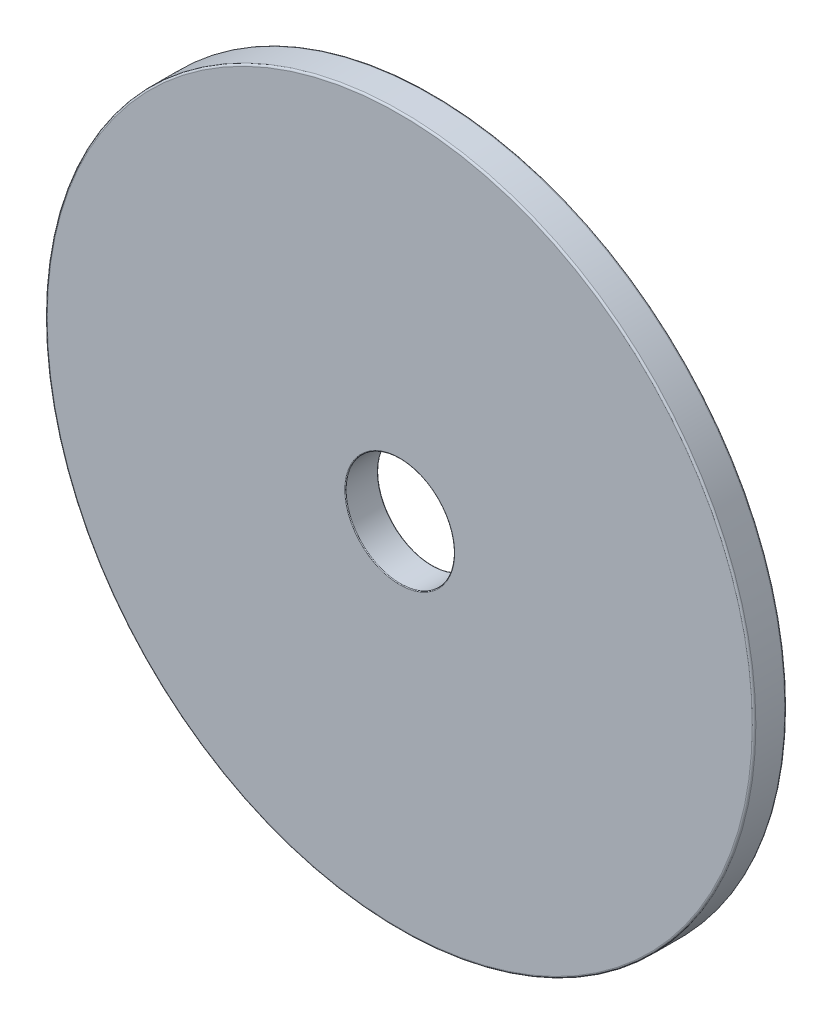
SolidWorks part; units mm, degrees
other "Markup1"
sketch "Sketch7" plane through (500, -500, -17.5) normal (0.1872, -0.6574, -0.7299) x (-0.982, -0.143, -0.123)
material "Portland Moderate Strength Concrete"
ref_plane "Front Plane" through (0, 0, 0) normal (0, 0, 1) x (1, 0, 0)
ref_plane "Top Plane" through (0, 0, 0) normal (0, 1, 0) x (1, 0, 0)
ref_plane "Right Plane" through (0, 0, 0) normal (1, 0, 0) x (0, 0, -1)
sketch "Sketch1" plane through (0, 0, 0) normal (0, 1, 0) x (1, 0, 0)
  line L0 (0, 58.8545) -> (0, -44.381) construction
  line L1 (-490, 20) -> (-490, -20)
  line L2 (-487.5, -22.5) -> (-150, -22.5)
  line L4 (47.8242, 0) -> (-116.8517, 0) construction
  line L5 (-487.5, 22.5) -> (-261, 22.5)
  line L8 (-76, 22.5) -> (-150, 22.5)
  line L15 (-76, -22.5) -> (-150, -22.5)
  line L16 (-75, 21.5) -> (-75, -21.5)
  line L17 (-260, 21.5) -> (-260, 13.5)
  line L18 (-259, 12.5) -> (-231, 12.5)
  line L19 (-230, 13.5) -> (-230, 21.5)
  line L20 (-229, 22.5) -> (-150, 22.5)
  arc A2 (-490, -20) -> (-487.5, -22.5) centre (-487.5, -20) ccw
  arc A3 (-490, 20) -> (-487.5, 22.5) centre (-487.5, 20) cw
  arc A4 (-76, -22.5) -> (-75, -21.5) centre (-76, -21.5) ccw
  arc A5 (-75, 21.5) -> (-76, 22.5) centre (-76, 21.5) ccw
  arc A6 (-229, 22.5) -> (-230, 21.5) centre (-229, 21.5) ccw
  arc A7 (-230, 13.5) -> (-231, 12.5) centre (-231, 13.5) cw
  arc A8 (-260, 13.5) -> (-259, 12.5) centre (-259, 13.5) ccw
  arc A9 (-261, 22.5) -> (-260, 21.5) centre (-261, 21.5) cw
  point P9 (-490, 0)
  point P29 (-230, 22.5)
  point P32 (-230, 12.5)
  point P35 (-260, 12.5)
  point P38 (-260, 22.5)
  dimension "D1" = 40
  dimension "D2" = 1
  dimension "D5" = 2.5
  dimension "D3" = 490
  dimension "D7" = 150
  dimension "D8" = 30
  dimension "D9" = 10
  dimension "D10" = 230
revolve "Revolve1" add sketch "Sketch1" angle 360 about L0
sketch "Sketch6" plane through (0, 0, -22.5) normal (0, 0, -1) x (-1, 0, 0)
  line L0 (0, 0) -> (-674.8433, 0) construction
  line L1 (-456.4497, 57.0406) -> (-357.3025, 43.9876)
  line L2 (-456.4497, -57.0406) -> (-357.3025, -43.9876)
  line L3 (-360, 0) -> (-360, 87.1924) construction
  line L4 (-423.8174, -178.8262) -> (-331.4269, -140.5568)
  line L5 (-366.7768, -277.6235) -> (-287.4392, -216.7457)
  line L6 (-426.1334, 173.2349) -> (-333.7429, 134.9655)
  line L7 (-455.6598, 63.0409) -> (-356.5126, 49.9879)
  line L8 (-366.7768, 277.6235) -> (-287.4392, 216.7457)
  line L9 (-423.8174, 178.8262) -> (-331.4269, 140.5568)
  line L10 (-282.4249, 363.0925) -> (-221.5471, 283.755)
  line L11 (-363.0925, 282.4249) -> (-283.755, 221.5471)
  line L12 (-178.8262, 423.8174) -> (-140.5568, 331.4269)
  line L13 (-277.6235, 366.7768) -> (-216.7457, 287.4392)
  line L14 (-63.0409, 455.6598) -> (-49.9879, 356.5126)
  line L15 (-173.2349, 426.1334) -> (-134.9655, 333.7429)
  line L16 (57.0406, 456.4497) -> (43.9876, 357.3025)
  line L17 (-57.0406, 456.4497) -> (-43.9876, 357.3025)
  line L18 (173.2349, 426.1334) -> (134.9655, 333.7429)
  line L19 (63.0409, 455.6598) -> (49.9879, 356.5126)
  line L20 (277.6235, 366.7768) -> (216.7457, 287.4392)
  line L21 (178.8262, 423.8174) -> (140.5568, 331.4269)
  line L22 (363.0925, 282.4249) -> (283.755, 221.5471)
  line L23 (282.4249, 363.0925) -> (221.5471, 283.755)
  line L24 (423.8174, 178.8262) -> (331.4269, 140.5568)
  line L25 (366.7768, 277.6235) -> (287.4392, 216.7457)
  line L26 (455.6598, 63.0409) -> (356.5126, 49.9879)
  line L27 (426.1334, 173.2349) -> (333.7429, 134.9655)
  line L28 (456.4497, -57.0406) -> (357.3025, -43.9876)
  line L29 (456.4497, 57.0406) -> (357.3025, 43.9876)
  line L30 (426.1334, -173.2349) -> (333.7429, -134.9655)
  line L31 (455.6598, -63.0409) -> (356.5126, -49.9879)
  line L32 (366.7768, -277.6235) -> (287.4392, -216.7457)
  line L33 (423.8174, -178.8262) -> (331.4269, -140.5568)
  line L34 (282.4249, -363.0925) -> (221.5471, -283.755)
  line L35 (363.0925, -282.4249) -> (283.755, -221.5471)
  line L36 (178.8262, -423.8174) -> (140.5568, -331.4269)
  line L37 (277.6235, -366.7768) -> (216.7457, -287.4392)
  line L38 (63.0409, -455.6598) -> (49.9879, -356.5126)
  line L39 (173.2349, -426.1334) -> (134.9655, -333.7429)
  line L40 (-57.0406, -456.4497) -> (-43.9876, -357.3025)
  line L41 (57.0406, -456.4497) -> (43.9876, -357.3025)
  line L42 (-173.2349, -426.1334) -> (-134.9655, -333.7429)
  line L43 (-63.0409, -455.6598) -> (-49.9879, -356.5126)
  line L44 (-277.6235, -366.7768) -> (-216.7457, -287.4392)
  line L45 (-178.8262, -423.8174) -> (-140.5568, -331.4269)
  line L46 (-363.0925, -282.4249) -> (-283.755, -221.5471)
  line L47 (-282.4249, -363.0925) -> (-221.5471, -283.755)
  line L48 (-455.6598, -63.0409) -> (-356.5126, -49.9879)
  line L49 (-426.1334, -173.2349) -> (-333.7429, -134.9655)
  arc A24 (-287.4392, -216.7457) -> (-331.4269, -140.5568) centre (0, 0) cw
  arc A25 (-456.4497, -57.0406) -> (-456.4497, 57.0406) centre (0, 0) cw
  arc A26 (-357.3025, -43.9876) -> (-357.3025, 43.9876) centre (0, 0) cw
  circle A27 centre (0, 0) radius 487.5 construction
  arc A28 (-356.5126, 49.9879) -> (-333.7429, 134.9655) centre (0, 0) cw
  arc A29 (-366.7768, -277.6235) -> (-423.8174, -178.8262) centre (0, 0) cw
  arc A30 (-455.6598, 63.0409) -> (-426.1334, 173.2349) centre (0, 0) cw
  arc A31 (-331.4269, 140.5568) -> (-287.4392, 216.7457) centre (0, 0) cw
  arc A32 (-423.8174, 178.8262) -> (-366.7768, 277.6235) centre (0, 0) cw
  arc A33 (-283.755, 221.5471) -> (-221.5471, 283.755) centre (0, 0) cw
  arc A34 (-363.0925, 282.4249) -> (-282.4249, 363.0925) centre (0, 0) cw
  arc A35 (-216.7457, 287.4392) -> (-140.5568, 331.4269) centre (0, 0) cw
  arc A36 (-277.6235, 366.7768) -> (-178.8262, 423.8174) centre (0, 0) cw
  arc A37 (-134.9655, 333.7429) -> (-49.9879, 356.5126) centre (0, 0) cw
  arc A38 (-173.2349, 426.1334) -> (-63.0409, 455.6598) centre (0, 0) cw
  arc A39 (-43.9876, 357.3025) -> (43.9876, 357.3025) centre (0, 0) cw
  arc A40 (-57.0406, 456.4497) -> (57.0406, 456.4497) centre (0, 0) cw
  arc A41 (49.9879, 356.5126) -> (134.9655, 333.7429) centre (0, 0) cw
  arc A42 (63.0409, 455.6598) -> (173.2349, 426.1334) centre (0, 0) cw
  arc A43 (140.5568, 331.4269) -> (216.7457, 287.4392) centre (0, 0) cw
  arc A44 (178.8262, 423.8174) -> (277.6235, 366.7768) centre (0, 0) cw
  arc A45 (221.5471, 283.755) -> (283.755, 221.5471) centre (0, 0) cw
  arc A46 (282.4249, 363.0925) -> (363.0925, 282.4249) centre (0, 0) cw
  arc A47 (287.4392, 216.7457) -> (331.4269, 140.5568) centre (0, 0) cw
  arc A48 (366.7768, 277.6235) -> (423.8174, 178.8262) centre (0, 0) cw
  arc A49 (333.7429, 134.9655) -> (356.5126, 49.9879) centre (0, 0) cw
  arc A50 (426.1334, 173.2349) -> (455.6598, 63.0409) centre (0, 0) cw
  arc A51 (357.3025, 43.9876) -> (357.3025, -43.9876) centre (0, 0) cw
  arc A52 (456.4497, 57.0406) -> (456.4497, -57.0406) centre (0, 0) cw
  arc A53 (356.5126, -49.9879) -> (333.7429, -134.9655) centre (0, 0) cw
  arc A54 (455.6598, -63.0409) -> (426.1334, -173.2349) centre (0, 0) cw
  arc A55 (331.4269, -140.5568) -> (287.4392, -216.7457) centre (0, 0) cw
  arc A56 (423.8174, -178.8262) -> (366.7768, -277.6235) centre (0, 0) cw
  arc A57 (283.755, -221.5471) -> (221.5471, -283.755) centre (0, 0) cw
  arc A58 (363.0925, -282.4249) -> (282.4249, -363.0925) centre (0, 0) cw
  arc A59 (216.7457, -287.4392) -> (140.5568, -331.4269) centre (0, 0) cw
  arc A60 (277.6235, -366.7768) -> (178.8262, -423.8174) centre (0, 0) cw
  arc A61 (134.9655, -333.7429) -> (49.9879, -356.5126) centre (0, 0) cw
  arc A62 (173.2349, -426.1334) -> (63.0409, -455.6598) centre (0, 0) cw
  arc A63 (43.9876, -357.3025) -> (-43.9876, -357.3025) centre (0, 0) cw
  arc A64 (57.0406, -456.4497) -> (-57.0406, -456.4497) centre (0, 0) cw
  arc A65 (-49.9879, -356.5126) -> (-134.9655, -333.7429) centre (0, 0) cw
  arc A66 (-63.0409, -455.6598) -> (-173.2349, -426.1334) centre (0, 0) cw
  arc A67 (-140.5568, -331.4269) -> (-216.7457, -287.4392) centre (0, 0) cw
  arc A68 (-178.8262, -423.8174) -> (-277.6235, -366.7768) centre (0, 0) cw
  arc A69 (-221.5471, -283.755) -> (-283.755, -221.5471) centre (0, 0) cw
  arc A70 (-282.4249, -363.0925) -> (-363.0925, -282.4249) centre (0, 0) cw
  arc A71 (-333.7429, -134.9655) -> (-356.5126, -49.9879) centre (0, 0) cw
  arc A72 (-426.1334, -173.2349) -> (-455.6598, -63.0409) centre (0, 0) cw
  point P114 (0, 0)
  dimension "D1" = 460
  dimension "D2" = 6.052
  dimension "D3" = 360
  dimension "D6" = 24
  dimension "D4" = 100.0028
extrude "Cut-Extrude1" cut sketch "Sketch6" against normal blind 20
